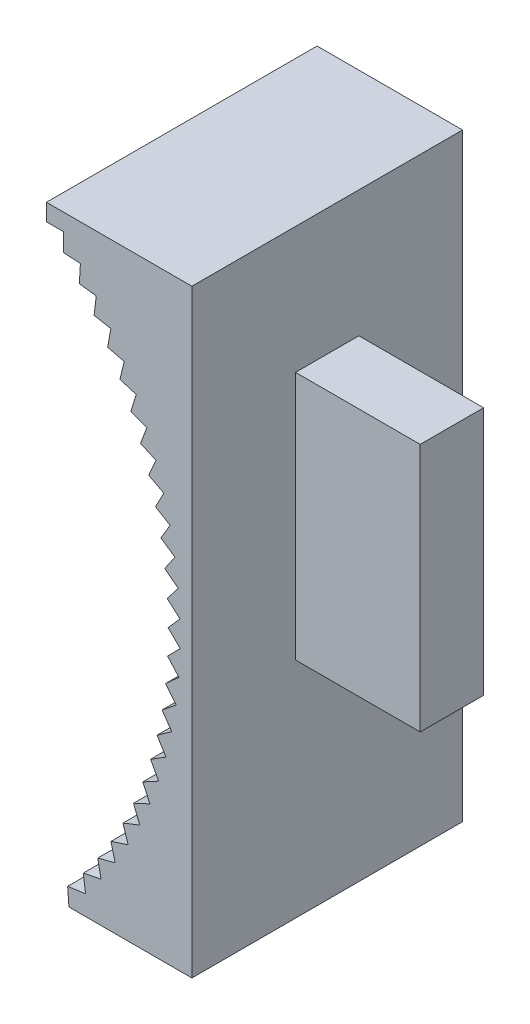
SolidWorks part; units mm, degrees
ref_plane "Front Plane" through (0, 0, 0) normal (0, 0, 1) x (1, 0, 0)
ref_plane "Top Plane" through (0, 0, 0) normal (0, 1, 0) x (1, 0, 0)
ref_plane "Right Plane" through (0, 0, 0) normal (1, 0, 0) x (0, 0, -1)
sketch "Sketch2" plane through (4.4293, 0, 0) normal (-1, 0, 0) x (0, 0, 1)
  line L8 (3.15, 99.7171) -> (0.1, 99.7171)
  line L9 (0.1, 99.7171) -> (0.1, 87.7296)
  line L10 (0.1, 87.7296) -> (3.15, 87.7296)
  line L11 (3.15, 87.7296) -> (3.15, 99.7171)
extrude "Boss-Extrude1" add sketch "Sketch2" against normal blind 6
sketch "Sketch3" plane through (4.4293, 0, 0) normal (-1, 0, 0) x (0, 0, 1)
  line L0 (8.1375, 105.8013) -> (-4.8875, 105.8013) construction
  line L1 (8.1375, 105.8013) -> (-4.8875, 105.8013)
  line L2 (-4.8875, 76.9688) -> (8.1375, 76.9688) construction
  line L3 (-4.8875, 76.9688) -> (8.1375, 76.9688)
  line L4 (-4.8875, 105.8013) -> (-4.8875, 76.9688)
  line L5 (8.1375, 105.8013) -> (8.1375, 76.9688)
extrude "Boss-Extrude2" add sketch "Sketch3" along normal blind 7
sketch "Sketch4" plane through (0, 0, -4.8875) normal (0, 0, -1) x (-1, 0, 0)
  line L4 (-4.4293, 105.8013) -> (-4.4293, 76.9688)
  line L5 (-4.4293, 76.9688) -> (2.5707, 76.9688)
  line L6 (2.5707, 76.9688) -> (2.5707, 105.8013)
  line L7 (2.5707, 105.8013) -> (-4.4293, 105.8013)
  line L9 (2.3046, 76.9688) -> (2.5707, 76.9688)
  line L10 (2.5707, 76.9688) -> (2.5707, 104.9852)
  arc A1 (2.5707, 104.9852) -> (2.3046, 76.9688) centre (16.7112, 90.8414) ccw
  dimension "D1" = 0
extrude "Cut-Extrude1" cut sketch "Sketch4" against normal through all
sketch "Sketch5" plane through (0, 0, -4.8875) normal (0, 0, -1) x (-1, 0, 0)
  line L6 (1.7546, 104.9852) -> (1.7546, 104.1192)
  line L7 (2.5707, 104.9852) -> (1.7546, 104.9852)
  line L166 (1.4893, 76.9836) -> (2.3528, 76.9189)
  line L167 (1.5502, 77.7974) -> (1.4893, 76.9836)
  line L168 (0.6877, 77.9187) -> (1.5459, 77.8025)
  line L169 (0.7973, 78.7275) -> (0.6877, 77.9187)
  line L170 (-0.0564, 78.9001) -> (0.7932, 78.7328)
  line L171 (0.1013, 79.7009) -> (-0.0564, 78.9001)
  line L172 (-0.7405, 79.9243) -> (0.0976, 79.7064)
  line L173 (-0.5352, 80.7141) -> (-0.7405, 79.9243)
  line L174 (-1.3622, 80.9875) -> (-0.5386, 80.7199)
  line L175 (-1.11, 81.7637) -> (-1.3622, 80.9875)
  line L176 (-1.9191, 82.086) -> (-1.113, 81.7696)
  line L177 (-1.621, 82.8457) -> (-1.9191, 82.086)
  line L178 (-2.4094, 83.2158) -> (-1.6237, 82.8518)
  line L179 (-2.0663, 83.9563) -> (-2.4094, 83.2158)
  line L180 (-2.8312, 84.373) -> (-2.0686, 83.9626)
  line L181 (-2.4445, 85.0916) -> (-2.8312, 84.373)
  line L182 (-3.1831, 85.5533) -> (-2.4464, 85.0981)
  line L183 (-2.7541, 86.2475) -> (-3.1831, 85.5533)
  line L184 (-3.4637, 86.7525) -> (-2.7556, 86.254)
  line L185 (-2.994, 87.4199) -> (-3.4637, 86.7525)
  line L186 (-3.6721, 87.9664) -> (-2.9951, 87.4264)
  line L187 (-3.1633, 88.6044) -> (-3.6721, 87.9664)
  line L188 (-3.8076, 89.1905) -> (-3.1641, 88.6111)
  line L189 (-3.2615, 89.797) -> (-3.8076, 89.1905)
  line L190 (-3.8696, 90.4206) -> (-3.2619, 89.8037)
  line L191 (-3.2882, 90.9933) -> (-3.8696, 90.4206)
  line L192 (-3.8579, 91.6522) -> (-3.2882, 91)
  line L193 (-3.2433, 92.1891) -> (-3.8579, 91.6522)
  line L194 (-3.7726, 92.8808) -> (-3.2429, 92.1958)
  line L195 (-3.127, 93.3801) -> (-3.7726, 92.8808)
  line L196 (-3.614, 94.1022) -> (-3.1262, 93.3867)
  line L197 (-2.9397, 94.5619) -> (-3.614, 94.1022)
  line L198 (-3.3826, 95.3119) -> (-2.9385, 94.5685)
  line L199 (-2.682, 95.7305) -> (-3.3826, 95.3119)
  line L200 (-3.0793, 96.5056) -> (-2.6804, 95.737)
  line L201 (-2.3549, 96.8815) -> (-3.0793, 96.5056)
  line L202 (-2.7051, 97.679) -> (-2.3529, 96.8879)
  line L203 (-1.9596, 98.0109) -> (-2.7051, 97.679)
  line L204 (-2.2615, 98.8279) -> (-1.9572, 98.0172)
  line L205 (-1.4974, 99.1147) -> (-2.2615, 98.8279)
  line L206 (-1.7499, 99.9483) -> (-1.4946, 99.1208)
  line L207 (-0.97, 100.1888) -> (-1.7499, 99.9483)
  line L208 (-1.1722, 101.036) -> (-0.9669, 100.1947)
  line L209 (-0.3794, 101.2295) -> (-1.1722, 101.036)
  line L210 (-0.5305, 102.0873) -> (-0.3759, 101.2352)
  line L211 (0.2725, 102.233) -> (-0.5305, 102.0873)
  line L212 (0.1729, 103.0983) -> (0.2763, 102.2385)
  line L213 (0.9832, 103.1957) -> (0.1729, 103.0983)
  line L214 (0.9355, 104.0654) -> (0.9873, 103.201)
  line L215 (1.7502, 104.1142) -> (0.9355, 104.0654)
  line L216 (3.5503, 106.6697) -> (3.4469, 105.81) [skipped]
  line L217 (4.3605, 106.5723) -> (3.5503, 106.6697) [skipped]
  line L218 (4.5204, 107.4285) -> (4.3658, 106.5764) [skipped]
  line L219 (5.3234, 107.2828) -> (4.5204, 107.4285) [skipped]
  line L220 (5.5342, 108.1279) -> (5.3289, 107.2866) [skipped]
  line L221 (6.3271, 107.9344) -> (5.5342, 108.1279) [skipped]
  line L222 (6.588, 108.7653) -> (6.3328, 107.9379) [skipped]
  line L223 (7.3679, 108.5248) -> (6.588, 108.7653) [skipped]
  line L224 (7.6781, 109.3387) -> (7.3738, 108.5279) [skipped]
  line L225 (8.4421, 109.0519) -> (7.6781, 109.3387) [skipped]
  line L226 (8.8005, 109.8458) -> (8.4482, 109.0547) [skipped]
  line L227 (9.546, 109.5138) -> (8.8005, 109.8458) [skipped]
  line L228 (9.9512, 110.2849) -> (9.5523, 109.5162) [skipped]
  line L229 (10.6755, 109.9089) -> (9.9512, 110.2849) [skipped]
  line L230 (11.1261, 110.6543) -> (10.6819, 109.9109) [skipped]
  line L231 (11.8266, 110.2358) -> (11.1261, 110.6543) [skipped]
  line L232 (12.321, 110.9529) -> (11.8331, 110.2374) [skipped]
  line L233 (12.9953, 110.4932) -> (12.321, 110.9529) [skipped]
  line L234 (13.5316, 111.1794) -> (13.0018, 110.4944) [skipped]
  line L235 (14.1772, 110.6802) -> (13.5316, 111.1794) [skipped]
  line L236 (14.7536, 111.3332) -> (14.1838, 110.6811) [skipped]
  line L237 (15.3681, 110.7963) -> (14.7536, 111.3332) [skipped]
  line L238 (15.9826, 111.4136) -> (15.3748, 110.7967) [skipped]
  line L239 (16.5639, 110.8409) -> (15.9826, 111.4136) [skipped]
  line L240 (17.2142, 111.4204) -> (16.5706, 110.8409) [skipped]
  line L241 (17.7602, 110.8139) -> (17.2142, 111.4204) [skipped]
  line L242 (18.444, 111.3534) -> (17.7669, 110.8135) [skipped]
  line L243 (18.9528, 110.7154) -> (18.444, 111.3534) [skipped]
  line L244 (19.6676, 111.2131) -> (18.9595, 110.7146) [skipped]
  line L245 (20.1373, 110.5458) -> (19.6676, 111.2131) [skipped]
  line L246 (20.8806, 110.9998) -> (20.1439, 110.5446) [skipped]
  line L247 (21.3096, 110.3056) -> (20.8806, 110.9998) [skipped]
  line L248 (22.0787, 110.7144) -> (21.3161, 110.304) [skipped]
  line L249 (22.4654, 109.9957) -> (22.0787, 110.7144) [skipped]
  line L250 (23.2576, 110.3578) -> (22.4718, 109.9938) [skipped]
  line L251 (23.6006, 109.6173) -> (23.2576, 110.3578) [skipped]
  line L252 (24.413, 109.9314) -> (23.6069, 109.615) [skipped]
  line L253 (24.7112, 109.1717) -> (24.413, 109.9314) [skipped]
  line L254 (25.5409, 109.4366) -> (24.7173, 109.169) [skipped]
  line L255 (25.7931, 108.6605) -> (25.5409, 109.4366) [skipped]
  line L256 (26.6372, 108.8753) -> (25.799, 108.6574) [skipped]
  line L257 (26.8425, 108.0854) -> (26.6372, 108.8753) [skipped]
  line L258 (27.6979, 108.2494) -> (26.8483, 108.0821) [skipped]
  line L259 (27.8556, 107.4487) -> (27.6979, 108.2494) [skipped]
  line L260 (28.7193, 107.5612) -> (27.8612, 107.445) [skipped]
  line L261 (28.8289, 106.7525) -> (28.7193, 107.5612) [skipped]
  line L262 (29.6977, 106.8131) -> (28.8342, 106.7484) [skipped]
  line L263 (29.7587, 105.9993) -> (29.6977, 106.8131) [skipped]
  line L264 (30.6297, 106.0079) -> (29.7638, 105.9949) [skipped]
  line L265 (30.6419, 105.1919) -> (30.6297, 106.0079) [skipped]
  line L266 (31.5118, 105.1484) -> (30.6467, 105.1872) [skipped]
  line L267 (31.4752, 104.3331) -> (31.5118, 105.1484) [skipped]
  line L268 (32.3409, 104.2376) -> (31.4797, 104.3282) [skipped]
  line L269 (32.2556, 103.426) -> (32.3409, 104.2376) [skipped]
  line L270 (33.1141, 103.2789) -> (32.2598, 103.4208) [skipped]
  line L271 (32.9804, 102.4739) -> (33.1141, 103.2789) [skipped]
  line L272 (33.8285, 102.2757) -> (32.9843, 102.4684) [skipped]
  line L273 (33.6469, 101.4801) -> (33.8285, 102.2757) [skipped]
  line L274 (34.4817, 101.2316) -> (33.6505, 101.4744) [skipped]
  line L275 (34.2528, 100.4482) -> (34.4817, 101.2316) [skipped]
  line L276 (35.0713, 100.1502) -> (34.2561, 100.4423) [skipped]
  line L277 (34.796, 99.3819) -> (35.0713, 100.1502) [skipped]
  line L278 (35.5951, 99.0355) -> (34.7988, 99.3759) [skipped]
  line L279 (35.2744, 98.2851) -> (35.5951, 99.0355) [skipped]
  line L280 (36.0514, 97.8915) -> (35.2769, 98.2789) [skipped]
  line L281 (35.6863, 97.1616) -> (36.0514, 97.8915) [skipped]
  line L282 (36.4384, 96.7223) -> (35.6884, 97.1553) [skipped]
  line L283 (36.0303, 96.0155) -> (36.4384, 96.7223) [skipped]
  line L284 (36.7548, 95.532) -> (36.032, 96.0091) [skipped]
  line L285 (36.3052, 94.8509) -> (36.7548, 95.532) [skipped]
  line L286 (36.9994, 94.3249) -> (36.3065, 94.8444) [skipped]
  line L287 (36.5099, 93.6719) -> (36.9994, 94.3249) [skipped]
  line L288 (37.1714, 93.1054) -> (36.5108, 93.6653) [skipped]
  line L289 (36.6437, 92.4828) -> (37.1714, 93.1054) [skipped]
  line L290 (37.2702, 91.8777) -> (36.6443, 92.4761) [skipped]
  line L291 (36.7062, 91.2878) -> (37.2702, 91.8777) [skipped]
  line L292 (37.2954, 90.6463) -> (36.7064, 91.2811) [skipped]
  line L293 (36.6971, 90.0913) -> (37.2954, 90.6463) [skipped]
  line L294 (37.2469, 89.4157) -> (36.6969, 90.0846) [skipped]
  line L295 (36.6165, 88.8974) -> (37.2469, 89.4157) [skipped]
  line L296 (37.1248, 88.1901) -> (36.6158, 88.8907) [skipped]
  line L297 (36.4646, 87.7104) -> (37.1248, 88.1901) [skipped]
  line L298 (36.9297, 86.974) -> (36.4636, 87.7038) [skipped]
  line L299 (36.242, 86.5347) -> (36.9297, 86.974) [skipped]
  line L300 (36.6623, 85.7718) -> (36.2406, 86.5281) [skipped]
  line L301 (35.9495, 85.3744) -> (36.6623, 85.7718) [skipped]
  line L302 (36.3234, 84.5877) -> (35.9477, 85.3679) [skipped]
  line L303 (35.5881, 84.2336) -> (36.3234, 84.5877) [skipped]
  line L304 (35.9143, 83.426) -> (35.5859, 84.2273) [skipped]
  line L305 (35.1591, 83.1165) -> (35.9143, 83.426) [skipped]
  line L306 (35.4364, 82.2909) -> (35.1566, 83.1104) [skipped]
  line L307 (34.6641, 82.0271) -> (35.4364, 82.2909) [skipped]
  line L308 (34.8916, 81.1863) -> (34.6612, 82.0211) [skipped]
  line L309 (34.1049, 80.9692) -> (34.8916, 81.1863) [skipped]
  line L310 (34.2816, 80.1163) -> (34.1016, 80.9634) [skipped]
  line L311 (33.4833, 79.9467) -> (34.2816, 80.1163) [skipped]
  line L312 (33.6088, 79.0848) -> (33.4797, 79.9411) [skipped]
  line L313 (32.8018, 78.9631) -> (33.6088, 79.0848) [skipped]
  line L314 (32.8754, 78.0953) -> (32.7978, 78.9577) [skipped]
  line L315 (32.0626, 78.0221) -> (32.8754, 78.0953) [skipped]
  line L316 (32.0842, 77.1514) -> (32.0583, 78.017) [skipped]
  line L317 (31.2685, 77.127) -> (32.0842, 77.1514) [skipped]
  line L318 (31.238, 76.2565) -> (31.2639, 77.1221) [skipped]
  line L319 (30.4222, 76.2809) -> (31.238, 76.2565) [skipped]
  line L320 (30.3397, 75.4139) -> (30.4174, 76.2763) [skipped]
  line L321 (29.5269, 75.487) -> (30.3397, 75.4139) [skipped]
  line L322 (29.3927, 74.6264) -> (29.5218, 75.4827) [skipped]
  line L323 (28.5857, 74.7481) -> (29.3927, 74.6264) [skipped]
  line L324 (28.4003, 73.897) -> (28.5803, 74.7441) [skipped]
  line L325 (27.602, 74.0667) -> (28.4003, 73.897) [skipped]
  line L326 (27.366, 73.2283) -> (27.5964, 74.0631) [skipped]
  line L327 (26.5793, 73.4454) -> (27.366, 73.2283) [skipped]
  line L328 (26.2936, 72.6226) -> (26.5735, 73.4421) [skipped]
  line L329 (25.5213, 72.8864) -> (26.2936, 72.6226) [skipped]
  line L330 (25.1869, 72.0822) -> (25.5153, 72.8835) [skipped]
  line L331 (24.4318, 72.3917) -> (25.1869, 72.0822) [skipped]
  line L332 (24.0499, 71.6089) -> (24.4256, 72.3891) [skipped]
  line L333 (23.3146, 71.963) -> (24.0499, 71.6089) [skipped]
  line L334 (22.8865, 71.2044) -> (23.3083, 71.9608) [skipped]
  line L335 (22.1738, 71.6018) -> (22.8865, 71.2044) [skipped]
  line L336 (21.7011, 70.8702) -> (22.1673, 71.6) [skipped]
  line L337 (21.0134, 71.3096) -> (21.7011, 70.8702) [skipped]
  line L338 (20.4978, 70.6076) -> (21.0068, 71.3082) [skipped]
  line L339 (19.8376, 71.0873) -> (20.4978, 70.6076) [skipped]
  line L340 (19.281, 70.4173) -> (19.831, 71.0862) [skipped]
  line L341 (18.6506, 70.9357) -> (19.281, 70.4173) [skipped]
  line L342 (18.0549, 70.3002) -> (18.644, 70.935) [skipped]
  line L343 (17.4567, 70.8553) -> (18.0549, 70.3002) [skipped]
  line L344 (16.8241, 70.2566) -> (17.45, 70.8551) [skipped]
  line L345 (16.2601, 70.8465) -> (16.8241, 70.2566) [skipped]
  line L346 (15.5928, 70.2867) -> (16.2534, 70.8466) [skipped]
  line L347 (15.0651, 70.9093) -> (15.5928, 70.2867) [skipped]
  line L348 (14.3656, 70.3904) -> (15.0585, 70.9098) [skipped]
  line L349 (13.8761, 71.0434) -> (14.3656, 70.3904) [skipped]
  line L350 (13.1467, 70.5673) -> (13.8694, 71.0443) [skipped]
  line L351 (12.6971, 71.2484) -> (13.1467, 70.5673) [skipped]
  line L352 (11.9406, 70.8167) -> (12.6906, 71.2497) [skipped]
  line L353 (11.5326, 71.5235) -> (11.9406, 70.8167) [skipped]
  line L354 (10.7516, 71.1379) -> (11.5261, 71.5252) [skipped]
  line L355 (10.3865, 71.8678) -> (10.7516, 71.1379) [skipped]
  line L356 (9.5839, 71.5295) -> (10.3802, 71.8699) [skipped]
  line L357 (9.2632, 72.28) -> (9.5839, 71.5295) [skipped]
  line L358 (8.4417, 71.9903) -> (9.257, 72.2825) [skipped]
  line L359 (8.1664, 72.7586) -> (8.4417, 71.9903) [skipped]
  line L360 (7.3292, 72.5186) -> (8.1604, 72.7615) [skipped]
  line L361 (7.1003, 73.302) -> (7.3292, 72.5186) [skipped]
  line L362 (6.2502, 73.1125) -> (7.0944, 73.3052) [skipped]
  line L363 (6.0686, 73.9082) -> (6.2502, 73.1125) [skipped]
  line L364 (5.2086, 73.7699) -> (6.0629, 73.9117) [skipped]
  line L365 (5.075, 74.5749) -> (5.2086, 73.7699) [skipped]
  line L366 (4.2083, 74.4883) -> (5.0695, 74.5788) [skipped]
  line L367 (4.123, 75.2999) -> (4.2083, 74.4883) [skipped]
  line L368 (3.2527, 75.2653) -> (4.1178, 75.3042) [skipped]
  line L369 (3.2161, 76.0806) -> (3.2527, 75.2653) [skipped]
  line L370 (2.3453, 76.0981) -> (3.2111, 76.0851) [skipped]
  line L371 (2.3575, 76.9141) -> (2.3453, 76.0981) [skipped]
  line L372 (2.6272, 105.8543) -> (2.5754, 104.9899) [skipped]
  line L373 (3.4419, 105.8055) -> (2.6272, 105.8543) [skipped]
  arc A0 (2.5707, 104.9852) -> (2.3046, 76.9688) centre (16.7112, 90.8414) ccw construction
  arc A1 (2.5707, 104.9852) -> (1.7546, 104.1192) centre (16.7112, 90.8414) ccw
  arc A81 (1.5502, 77.7974) -> (2.3528, 76.9189) centre (16.7112, 90.8414) ccw
  arc A82 (0.7973, 78.7275) -> (1.5459, 77.8025) centre (16.7112, 90.8414) ccw
  arc A83 (0.1013, 79.7009) -> (0.7932, 78.7328) centre (16.7112, 90.8414) ccw
  arc A84 (-0.5352, 80.7141) -> (0.0976, 79.7064) centre (16.7112, 90.8414) ccw
  arc A85 (-1.11, 81.7637) -> (-0.5386, 80.7199) centre (16.7112, 90.8414) ccw
  arc A86 (-1.621, 82.8457) -> (-1.113, 81.7696) centre (16.7112, 90.8414) ccw
  arc A87 (-2.0663, 83.9563) -> (-1.6237, 82.8518) centre (16.7112, 90.8414) ccw
  arc A88 (-2.4445, 85.0916) -> (-2.0686, 83.9626) centre (16.7112, 90.8414) ccw
  arc A89 (-2.7541, 86.2475) -> (-2.4464, 85.0981) centre (16.7112, 90.8414) ccw
  arc A90 (-2.994, 87.4199) -> (-2.7556, 86.254) centre (16.7112, 90.8414) ccw
  arc A91 (-3.1633, 88.6044) -> (-2.9951, 87.4264) centre (16.7112, 90.8414) ccw
  arc A92 (-3.2615, 89.797) -> (-3.1641, 88.6111) centre (16.7112, 90.8414) ccw
  arc A93 (-3.2882, 90.9933) -> (-3.2619, 89.8037) centre (16.7112, 90.8414) ccw
  arc A94 (-3.2433, 92.1891) -> (-3.2882, 91) centre (16.7112, 90.8414) ccw
  arc A95 (-3.127, 93.3801) -> (-3.2429, 92.1958) centre (16.7112, 90.8414) ccw
  arc A96 (-2.9397, 94.5619) -> (-3.1262, 93.3867) centre (16.7112, 90.8414) ccw
  arc A97 (-2.682, 95.7305) -> (-2.9385, 94.5685) centre (16.7112, 90.8414) ccw
  arc A98 (-2.3549, 96.8815) -> (-2.6804, 95.737) centre (16.7112, 90.8414) ccw
  arc A99 (-1.9596, 98.0109) -> (-2.3529, 96.8879) centre (16.7112, 90.8414) ccw
  arc A100 (-1.4974, 99.1147) -> (-1.9572, 98.0172) centre (16.7112, 90.8414) ccw
  arc A101 (-0.97, 100.1888) -> (-1.4946, 99.1208) centre (16.7112, 90.8414) ccw
  arc A102 (-0.3794, 101.2295) -> (-0.9669, 100.1947) centre (16.7112, 90.8414) ccw
  arc A103 (0.2725, 102.233) -> (-0.3759, 101.2352) centre (16.7112, 90.8414) ccw
  arc A104 (0.9832, 103.1957) -> (0.2763, 102.2385) centre (16.7112, 90.8414) ccw
  arc A105 (1.7502, 104.1142) -> (0.9873, 103.201) centre (16.7112, 90.8414) ccw
  arc A106 (4.3605, 106.5723) -> (3.4469, 105.81) centre (16.7112, 90.8414) ccw [skipped]
  arc A107 (5.3234, 107.2828) -> (4.3658, 106.5764) centre (16.7112, 90.8414) ccw [skipped]
  arc A108 (6.3271, 107.9344) -> (5.3289, 107.2866) centre (16.7112, 90.8414) ccw [skipped]
  arc A109 (7.3679, 108.5248) -> (6.3328, 107.9379) centre (16.7112, 90.8414) ccw [skipped]
  arc A110 (8.4421, 109.0519) -> (7.3738, 108.5279) centre (16.7112, 90.8414) ccw [skipped]
  arc A111 (9.546, 109.5138) -> (8.4482, 109.0547) centre (16.7112, 90.8414) ccw [skipped]
  arc A112 (10.6755, 109.9089) -> (9.5523, 109.5162) centre (16.7112, 90.8414) ccw [skipped]
  arc A113 (11.8266, 110.2358) -> (10.6819, 109.9109) centre (16.7112, 90.8414) ccw [skipped]
  arc A114 (12.9953, 110.4932) -> (11.8331, 110.2374) centre (16.7112, 90.8414) ccw [skipped]
  arc A115 (14.1772, 110.6802) -> (13.0018, 110.4944) centre (16.7112, 90.8414) ccw [skipped]
  arc A116 (15.3681, 110.7963) -> (14.1838, 110.6811) centre (16.7112, 90.8414) ccw [skipped]
  arc A117 (16.5639, 110.8409) -> (15.3748, 110.7967) centre (16.7112, 90.8414) ccw [skipped]
  arc A118 (17.7602, 110.8139) -> (16.5706, 110.8409) centre (16.7112, 90.8414) ccw [skipped]
  arc A119 (18.9528, 110.7154) -> (17.7669, 110.8135) centre (16.7112, 90.8414) ccw [skipped]
  arc A120 (20.1373, 110.5458) -> (18.9595, 110.7146) centre (16.7112, 90.8414) ccw [skipped]
  arc A121 (21.3096, 110.3056) -> (20.1439, 110.5446) centre (16.7112, 90.8414) ccw [skipped]
  arc A122 (22.4654, 109.9957) -> (21.3161, 110.304) centre (16.7112, 90.8414) ccw [skipped]
  arc A123 (23.6006, 109.6173) -> (22.4718, 109.9938) centre (16.7112, 90.8414) ccw [skipped]
  arc A124 (24.7112, 109.1717) -> (23.6069, 109.615) centre (16.7112, 90.8414) ccw [skipped]
  arc A125 (25.7931, 108.6605) -> (24.7173, 109.169) centre (16.7112, 90.8414) ccw [skipped]
  arc A126 (26.8425, 108.0854) -> (25.799, 108.6574) centre (16.7112, 90.8414) ccw [skipped]
  arc A127 (27.8556, 107.4487) -> (26.8483, 108.0821) centre (16.7112, 90.8414) ccw [skipped]
  arc A128 (28.8289, 106.7525) -> (27.8612, 107.445) centre (16.7112, 90.8414) ccw [skipped]
  arc A129 (29.7587, 105.9993) -> (28.8342, 106.7484) centre (16.7112, 90.8414) ccw [skipped]
  arc A130 (30.6419, 105.1919) -> (29.7638, 105.9949) centre (16.7112, 90.8414) ccw [skipped]
  arc A131 (31.4752, 104.3331) -> (30.6467, 105.1872) centre (16.7112, 90.8414) ccw [skipped]
  arc A132 (32.2556, 103.426) -> (31.4797, 104.3282) centre (16.7112, 90.8414) ccw [skipped]
  arc A133 (32.9804, 102.4739) -> (32.2598, 103.4208) centre (16.7112, 90.8414) ccw [skipped]
  arc A134 (33.6469, 101.4801) -> (32.9843, 102.4684) centre (16.7112, 90.8414) ccw [skipped]
  arc A135 (34.2528, 100.4482) -> (33.6505, 101.4744) centre (16.7112, 90.8414) ccw [skipped]
  arc A136 (34.796, 99.3819) -> (34.2561, 100.4423) centre (16.7112, 90.8414) ccw [skipped]
  arc A137 (35.2744, 98.2851) -> (34.7988, 99.3759) centre (16.7112, 90.8414) ccw [skipped]
  arc A138 (35.6863, 97.1616) -> (35.2769, 98.2789) centre (16.7112, 90.8414) ccw [skipped]
  arc A139 (36.0303, 96.0155) -> (35.6884, 97.1553) centre (16.7112, 90.8414) ccw [skipped]
  arc A140 (36.3052, 94.8509) -> (36.032, 96.0091) centre (16.7112, 90.8414) ccw [skipped]
  arc A141 (36.5099, 93.6719) -> (36.3065, 94.8444) centre (16.7112, 90.8414) ccw [skipped]
  arc A142 (36.6437, 92.4828) -> (36.5108, 93.6653) centre (16.7112, 90.8414) ccw [skipped]
  arc A143 (36.7062, 91.2878) -> (36.6443, 92.4761) centre (16.7112, 90.8414) ccw [skipped]
  arc A144 (36.6971, 90.0913) -> (36.7064, 91.2811) centre (16.7112, 90.8414) ccw [skipped]
  arc A145 (36.6165, 88.8974) -> (36.6969, 90.0846) centre (16.7112, 90.8414) ccw [skipped]
  arc A146 (36.4646, 87.7104) -> (36.6158, 88.8907) centre (16.7112, 90.8414) ccw [skipped]
  arc A147 (36.242, 86.5347) -> (36.4636, 87.7038) centre (16.7112, 90.8414) ccw [skipped]
  arc A148 (35.9495, 85.3744) -> (36.2406, 86.5281) centre (16.7112, 90.8414) ccw [skipped]
  arc A149 (35.5881, 84.2336) -> (35.9477, 85.3679) centre (16.7112, 90.8414) ccw [skipped]
  arc A150 (35.1591, 83.1165) -> (35.5859, 84.2273) centre (16.7112, 90.8414) ccw [skipped]
  arc A151 (34.6641, 82.0271) -> (35.1566, 83.1104) centre (16.7112, 90.8414) ccw [skipped]
  arc A152 (34.1049, 80.9692) -> (34.6612, 82.0211) centre (16.7112, 90.8414) ccw [skipped]
  arc A153 (33.4833, 79.9467) -> (34.1016, 80.9634) centre (16.7112, 90.8414) ccw [skipped]
  arc A154 (32.8018, 78.9631) -> (33.4797, 79.9411) centre (16.7112, 90.8414) ccw [skipped]
  arc A155 (32.0626, 78.0221) -> (32.7978, 78.9577) centre (16.7112, 90.8414) ccw [skipped]
  arc A156 (31.2685, 77.127) -> (32.0583, 78.017) centre (16.7112, 90.8414) ccw [skipped]
  arc A157 (30.4222, 76.2809) -> (31.2639, 77.1221) centre (16.7112, 90.8414) ccw [skipped]
  arc A158 (29.5269, 75.487) -> (30.4174, 76.2763) centre (16.7112, 90.8414) ccw [skipped]
  arc A159 (28.5857, 74.7481) -> (29.5218, 75.4827) centre (16.7112, 90.8414) ccw [skipped]
  arc A160 (27.602, 74.0667) -> (28.5803, 74.7441) centre (16.7112, 90.8414) ccw [skipped]
  arc A161 (26.5793, 73.4454) -> (27.5964, 74.0631) centre (16.7112, 90.8414) ccw [skipped]
  arc A162 (25.5213, 72.8864) -> (26.5735, 73.4421) centre (16.7112, 90.8414) ccw [skipped]
  arc A163 (24.4318, 72.3917) -> (25.5153, 72.8835) centre (16.7112, 90.8414) ccw [skipped]
  arc A164 (23.3146, 71.963) -> (24.4256, 72.3891) centre (16.7112, 90.8414) ccw [skipped]
  arc A165 (22.1738, 71.6018) -> (23.3083, 71.9608) centre (16.7112, 90.8414) ccw [skipped]
  arc A166 (21.0134, 71.3096) -> (22.1673, 71.6) centre (16.7112, 90.8414) ccw [skipped]
  arc A167 (19.8376, 71.0873) -> (21.0068, 71.3082) centre (16.7112, 90.8414) ccw [skipped]
  arc A168 (18.6506, 70.9357) -> (19.831, 71.0862) centre (16.7112, 90.8414) ccw [skipped]
  arc A169 (17.4567, 70.8553) -> (18.644, 70.935) centre (16.7112, 90.8414) ccw [skipped]
  arc A170 (16.2601, 70.8465) -> (17.45, 70.8551) centre (16.7112, 90.8414) ccw [skipped]
  arc A171 (15.0651, 70.9093) -> (16.2534, 70.8466) centre (16.7112, 90.8414) ccw [skipped]
  arc A172 (13.8761, 71.0434) -> (15.0585, 70.9098) centre (16.7112, 90.8414) ccw [skipped]
  arc A173 (12.6971, 71.2484) -> (13.8694, 71.0443) centre (16.7112, 90.8414) ccw [skipped]
  arc A174 (11.5326, 71.5235) -> (12.6906, 71.2497) centre (16.7112, 90.8414) ccw [skipped]
  arc A175 (10.3865, 71.8678) -> (11.5261, 71.5252) centre (16.7112, 90.8414) ccw [skipped]
  arc A176 (9.2632, 72.28) -> (10.3802, 71.8699) centre (16.7112, 90.8414) ccw [skipped]
  arc A177 (8.1664, 72.7586) -> (9.257, 72.2825) centre (16.7112, 90.8414) ccw [skipped]
  arc A178 (7.1003, 73.302) -> (8.1604, 72.7615) centre (16.7112, 90.8414) ccw [skipped]
  arc A179 (6.0686, 73.9082) -> (7.0944, 73.3052) centre (16.7112, 90.8414) ccw [skipped]
  arc A180 (5.075, 74.5749) -> (6.0629, 73.9117) centre (16.7112, 90.8414) ccw [skipped]
  arc A181 (4.123, 75.2999) -> (5.0695, 74.5788) centre (16.7112, 90.8414) ccw [skipped]
  arc A182 (3.2161, 76.0806) -> (4.1178, 75.3042) centre (16.7112, 90.8414) ccw [skipped]
  arc A183 (2.3575, 76.9141) -> (3.2111, 76.0851) centre (16.7112, 90.8414) ccw [skipped]
  arc A184 (3.4419, 105.8055) -> (2.5754, 104.9899) centre (16.7112, 90.8414) ccw [skipped]
  dimension "D1" = 105
extrude "Cut-Extrude2" cut sketch "Sketch5" against normal through all
sketch "Sketch6" plane through (0, 0, -4.8875) normal (0, 0, -1) x (-1, 0, 0)
  line L0 (1.4893, 76.9836) -> (1.4882, 76.9688)
  line L1 (1.4893, 76.9836) -> (1.6865, 76.9688) construction
  line L2 (1.4893, 76.9836) -> (1.6865, 76.9688)
  line L3 (1.6865, 76.9688) -> (-4.4293, 76.9688) construction
  line L4 (1.6865, 76.9688) -> (1.4882, 76.9688)
extrude "Cut-Extrude5" cut sketch "Sketch6" against normal through all
